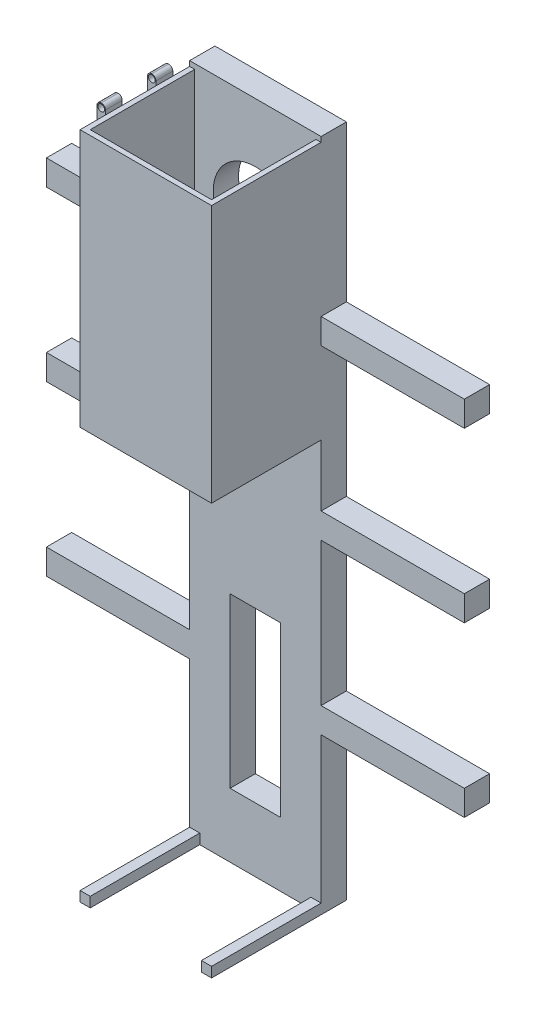
SolidWorks part; units mm, degrees
ref_plane "Ön Düzlem" through (0, 0, 0) normal (0, 0, 1) x (1, 0, 0)
ref_plane "Üst Düzlem" through (0, 0, 0) normal (0, 1, 0) x (1, 0, 0)
ref_plane "Sağ Düzlem" through (0, 0, 0) normal (1, 0, 0) x (0, 0, -1)
sketch "Çizim1" plane through (0, 0, 0) normal (0, 0, 1) x (1, 0, 0)
  line L0 (0, 0) -> (78, 0)
  line L1 (78, 0) -> (78, -400)
  line L2 (78, -400) -> (0, -400)
  line L3 (0, -400) -> (0, 0)
  dimension "D1" = 78
  dimension "D2" = 400
extrude "Yükseklik-Ekstrüzyon1" add sketch "Çizim1" along normal blind 15
sketch "Çizim2" plane through (0, 0, 15) normal (0, 0, 1) x (1, 0, 0)
  line L0 (78, 0) -> (0, 0) construction
  circle A0 centre (39, -60) radius 25
  dimension "D1" = 60
extrude "Kes-Ekstrüzyon1" cut sketch "Çizim2" against normal blind 30
sketch "Çizim3" plane through (0, 0, 0) normal (-1, 0, 0) x (0, 0, 1)
  line L0 (15, 0) -> (0, 0) construction
  line L1 (15, 0) -> (15, -400) construction
  line L2 (0, -207.5) -> (15, -207.5)
  line L3 (15, -92.5) -> (15, -107.5)
  line L4 (0, 0) -> (0, -400) construction
  line L6 (15, -92.5) -> (0, -92.5)
  line L7 (0, -92.5) -> (0, -107.5)
  line L8 (0, -107.5) -> (15, -107.5)
  line L12 (0, -207.5) -> (0, -192.5)
  line L13 (0, -192.5) -> (15, -192.5)
  line L14 (15, -192.5) -> (15, -207.5)
  line L17 (15, -292.5) -> (15, -307.5)
  line L18 (15, -307.5) -> (0, -307.5)
  line L19 (0, -307.5) -> (0, -292.5)
  line L20 (0, -292.5) -> (15, -292.5)
  dimension "D2" = 92.5
  dimension "D3" = 15
  dimension "D4" = 15
  dimension "D6" = 15
extrude "Yükseklik-Ekstrüzyon2" add sketch "Çizim3" against normal blind 163 and the other way blind 85
sketch "Çizim4" plane through (0, 0, 15) normal (0, 0, 1) x (1, 0, 0)
  line L0 (39, -400) -> (39, -361.9959)
  line L1 (0, -400) -> (78, -400) construction
  line L2 (39, -361.9959) -> (54, -361.9959)
  line L3 (54, -361.9959) -> (54, -261.9959)
  line L4 (54, -261.9959) -> (24, -261.9959)
  line L5 (24, -261.9959) -> (24, -361.9959)
  line L6 (24, -361.9959) -> (39, -361.9959)
  dimension "D1" = 15
  dimension "D2" = 15
  dimension "D3" = 100
  dimension "D4" = 38.0041
extrude "Kes-Ekstrüzyon2" cut sketch "Çizim4" against normal blind 26 contours L5 L6 L2 L3 L4
sketch "Çizim5" plane through (0, 0, 15) normal (0, 0, 1) x (1, 0, 0)
  line L2 (75, -3) -> (78, -3)
  line L4 (3, -3) -> (0, -3)
  line L6 (0, -400) -> (6, -400)
  line L8 (75, -3) -> (75, -153)
  line L9 (75, -153) -> (3, -153)
  line L10 (3, -153) -> (3, -3)
  line L12 (0, -400) -> (78, -400) construction
  line L13 (6, -400) -> (6, -394)
  line L14 (6, -394) -> (0, -394)
  line L15 (0, -307.5) -> (0, -400) construction
  line L16 (0, -394) -> (0, -400)
  line L17 (78, -400) -> (72, -400)
  line L18 (72, -400) -> (72, -394)
  line L19 (72, -394) -> (78, -394)
  line L20 (78, -400) -> (78, -307.5) construction
  line L21 (78, -394) -> (78, -400)
  line L23 (0, -107.5) -> (0, -192.5) construction
  line L24 (0, -156) -> (78, -156)
  line L25 (78, -192.5) -> (78, -107.5) construction
  line L27 (78, -3) -> (78, -156)
  line L28 (0, -3) -> (0, -156)
  dimension "D1" = 6
  dimension "D3" = 150
  dimension "D4" = 3
  dimension "D5" = 6
  dimension "D6" = 6
  dimension "D7" = 6
extrude "Yükseklik-Ekstrüzyon3" add sketch "Çizim5" along normal blind 65
sketch "Çizim6" plane through (0, 0, 0) normal (0, 0, -1) x (-1, 0, 0)
  line L0 (-78, 0) -> (0, 0) construction
  circle A0 centre (-39, -140) radius 7
  dimension "D1" = 140
extrude "Kes-Ekstrüzyon3" cut sketch "Çizim6" against normal blind 65
sketch "Çizim8" plane through (0, -153, 0) normal (0, 1, 0) x (1, 0, 0)
  line L0 (3, -80) -> (3, -77)
  line L1 (3, -80) -> (3, -15) construction
  line L2 (3, -77) -> (75, -77)
  line L3 (75, -80) -> (75, -15) construction
  line L4 (75, -77) -> (75, -80)
  line L5 (75, -80) -> (75, -15) construction
  line L6 (75, -80) -> (3, -80)
  dimension "D1" = 3
extrude "Yükseklik-Ekstrüzyon4" add sketch "Çizim8" along normal blind 150
sketch "Çizim9" plane through (0, 0, 0) normal (-1, 0, 0) x (0, 0, 1)
  line L0 (65, -3) -> (65, -8)
  line L1 (80, -3) -> (15, -3) construction
  line L2 (65, -8) -> (55, -8)
  line L3 (55, -8) -> (55, -3)
  line L4 (55, -3) -> (65, -3)
  line L5 (35, -3) -> (35, -8)
  line L6 (35, -8) -> (25, -8)
  line L7 (25, -8) -> (25, -3)
  line L8 (25, -3) -> (35, -3)
  line L9 (80, -3) -> (80, -156) construction
  point P12 (35, -5.5)
  dimension "D1" = 15
  dimension "D2" = 5
  dimension "D3" = 20
  dimension "D4" = 10
  dimension "D5" = 10
  dimension "D6" = 5
extrude "Yükseklik-Ekstrüzyon5" add sketch "Çizim9" along normal blind 5
sketch "Çizim12" plane through (0, -3, 0) normal (0, 1, 0) x (1, 0, 0)
  line L0 (-5, -25) -> (0, -25)
  line L1 (0, -25) -> (0, -35)
  line L2 (0, -35) -> (-5, -35)
  line L3 (-5, -35) -> (-5, -25)
  line L4 (-5, -55) -> (0, -55)
  line L5 (0, -55) -> (0, -65)
  line L6 (0, -65) -> (-5, -65)
  line L7 (-5, -65) -> (-5, -55)
extrude "Yükseklik-Ekstrüzyon6" add sketch "Çizim12" along normal blind 5
sketch "Çizim13" plane through (0, 0, 65) normal (0, 0, 1) x (1, 0, 0)
  line L0 (-5, -8) -> (0, -8)
  line L1 (0, -8) -> (0, -13)
  line L2 (0, -3) -> (0, -156) construction
  line L3 (0, -13) -> (-5, -8)
  dimension "D1" = 5
extrude "Yükseklik-Ekstrüzyon7" add sketch "Çizim13" against normal blind 10
sketch "Çizim14" plane through (0, 0, 25) normal (0, 0, -1) x (-1, 0, 0)
  line L0 (0, -8) -> (0, -13)
  line L1 (0, -3) -> (0, -13) construction
  line L2 (0, -13) -> (5, -8)
  line L3 (5, -8) -> (0, -8)
extrude "Yükseklik-Ekstrüzyon8" add sketch "Çizim14" against normal blind 10
sketch "Çizim15" plane through (0, 0, 25) normal (0, 0, -1) x (-1, 0, 0)
  circle A0 centre (2.5, -0.5) radius 2
extrude "Kes-Ekstrüzyon5" cut sketch "Çizim15" against normal blind 46
fillet "Radyus1" radius 2.4 1 edges at (0, 2, 60)
fillet "Radyus2" radius 2.4 1 edges at (0, 2, 30)
fillet "Radyus3" radius 2.4 1 edges at (-5, 2, 30)
fillet "Radyus4" radius 2.4 1 edges at (-5, 2, 60)
